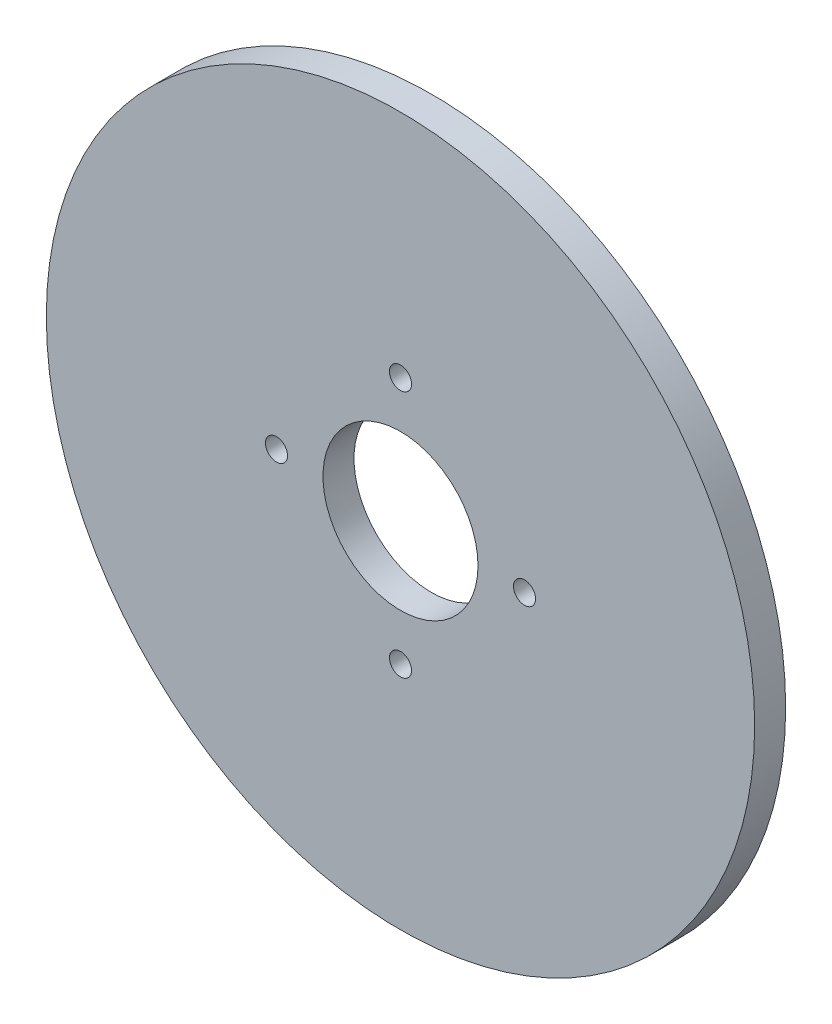
SolidWorks part; units mm, degrees
material "6061 Alloy"
ref_plane "Front Plane" through (0, 0, 0) normal (0, 0, 1) x (1, 0, 0)
ref_plane "Top Plane" through (0, 0, 0) normal (0, 1, 0) x (1, 0, 0)
ref_plane "Right Plane" through (0, 0, 0) normal (1, 0, 0) x (0, 0, -1)
sketch "Sketch1" plane through (0, 0, 0) normal (0, 0, 1) x (1, 0, 0)
  circle A0 centre (0, 0) radius 36.2712
  circle A1 centre (0, 0) radius 7.9375
  dimension "D1" = 72.5424
  dimension "D2" = 15.875
extrude "Boss-Extrude1" add sketch "Sketch1" along normal blind 3.175
hole_wizard "Tap Drill for #4-40 Tap1" positions "Sketch2" profile "Sketch3" hole size "#4-40" standard "ANSI Inch"
sketch "Sketch2" plane through (0, 0, 3.175) normal (0, 0, 1) x (1, 0, 0)
  point P0 (0, 12.7)
  point P2 (0, -12.7)
  point P4 (12.7, 0)
  point P6 (-12.7, 0)
  dimension "D1" = 12.7
  dimension "D2" = 12.7
  dimension "D3" = 12.7
  dimension "D4" = 12.7
sketch "Sketch3" plane through (0, 12.7, 3.175) normal (1, 0, 0) x (0, -1, 0)
  line L0 (0, 0) -> (0, 4.6792)
  line L1 (0, 4.6792) -> (1.1303, 4)
  line L2 (1.1303, 4) -> (1.1303, 0)
  line L5 (1.1303, 0) -> (0, 0)
  line L10 (0, 4.6792) -> (-1.1303, 4) construction
  line L11 (0, -6.35) -> (0, 107.95) construction
  dimension "Hole Dia." = 2.2606
  dimension "Hole Depth" = 4
  dimension "Drill Angle" = 118
